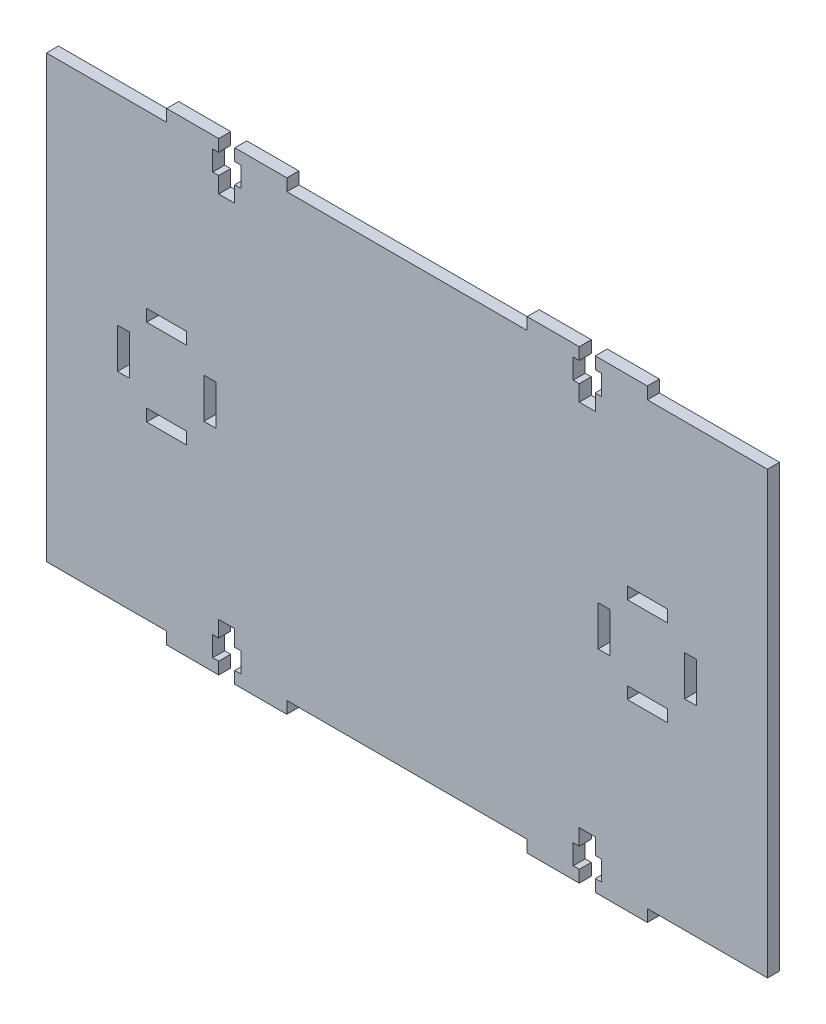
SolidWorks part; units mm, degrees
ref_plane "Front Plane" through (0, 0, 0) normal (0, 0, 1) x (1, 0, 0)
ref_plane "Top Plane" through (0, 0, 0) normal (0, 1, 0) x (1, 0, 0)
ref_plane "Right Plane" through (0, 0, 0) normal (1, 0, 0) x (0, 0, -1)
sketch "Sketch1" plane through (0, 0, 0) normal (0, 0, 1) x (1, 0, 0)
  line L0 (30, -55) -> (-30, -55)
  line L1 (-30, -55) -> (-30, -58)
  line L2 (30, -58) -> (30, -55)
  line L3 (-30, -58) -> (-43, -58)
  line L4 (43, -58) -> (30, -58)
  line L5 (-43, -58) -> (-43, -55)
  line L6 (43, -55) -> (43, -58)
  line L7 (-43, -55) -> (-41.5, -55)
  line L8 (41.5, -55) -> (43, -55)
  line L9 (-41.5, -55) -> (-41.5, -50)
  line L10 (41.5, -50) -> (41.5, -55)
  line L11 (-41.5, -50) -> (-43, -50)
  line L12 (43, -50) -> (41.5, -50)
  line L13 (-43, -50) -> (-43, -46)
  line L14 (43, -46) -> (43, -50)
  line L15 (-43, -46) -> (-47, -46)
  line L16 (47, -46) -> (43, -46)
  line L17 (-47, -46) -> (-47, -50)
  line L18 (47, -50) -> (47, -46)
  line L19 (-47, -50) -> (-48.5, -50)
  line L20 (48.5, -50) -> (47, -50)
  line L21 (-48.5, -50) -> (-48.5, -55)
  line L22 (48.5, -55) -> (48.5, -50)
  line L23 (-48.5, -55) -> (-47, -55)
  line L24 (47, -55) -> (48.5, -55)
  line L25 (-47, -55) -> (-47, -58)
  line L26 (47, -58) -> (47, -55)
  line L27 (-47, -58) -> (-60, -58)
  line L28 (60, -58) -> (47, -58)
  line L29 (-60, -58) -> (-60, -55)
  line L30 (60, -55) -> (60, -58)
  line L31 (-60, -55) -> (-90, -55)
  line L32 (90, -55) -> (60, -55)
  line L33 (-90, -55) -> (-90, 55)
  line L34 (90, 55) -> (90, -55)
  line L35 (-90, 55) -> (-60, 55)
  line L36 (60, 55) -> (90, 55)
  line L37 (-60, 55) -> (-60, 58)
  line L38 (60, 58) -> (60, 55)
  line L39 (-60, 58) -> (-47, 58)
  line L40 (47, 58) -> (60, 58)
  line L41 (-47, 58) -> (-47, 55)
  line L42 (47, 55) -> (47, 58)
  line L43 (-47, 55) -> (-48.5, 55)
  line L44 (48.5, 55) -> (47, 55)
  line L45 (-48.5, 55) -> (-48.5, 50)
  line L46 (48.5, 50) -> (48.5, 55)
  line L47 (-48.5, 50) -> (-47, 50)
  line L48 (47, 50) -> (48.5, 50)
  line L49 (-47, 50) -> (-47, 46)
  line L50 (47, 46) -> (47, 50)
  line L51 (-47, 46) -> (-43, 46)
  line L52 (43, 46) -> (47, 46)
  line L53 (-43, 46) -> (-43, 50)
  line L54 (43, 50) -> (43, 46)
  line L55 (-43, 50) -> (-41.5, 50)
  line L56 (41.5, 50) -> (43, 50)
  line L57 (-41.5, 50) -> (-41.5, 55)
  line L58 (41.5, 55) -> (41.5, 50)
  line L59 (-41.5, 55) -> (-43, 55)
  line L60 (43, 55) -> (41.5, 55)
  line L61 (-43, 55) -> (-43, 58)
  line L62 (43, 58) -> (43, 55)
  line L63 (-43, 58) -> (-30, 58)
  line L64 (30, 58) -> (43, 58)
  line L65 (-30, 58) -> (-30, 55)
  line L66 (30, 55) -> (30, 58)
  line L67 (-30, 55) -> (30, 55)
  line L68 (-61.5, -12.285) -> (-58.5, -12.285)
  line L69 (-58.5, -12.285) -> (-58.5, -9.285)
  line L70 (-61.5, -9.285) -> (-61.5, -12.285)
  line L71 (-58.5, -9.285) -> (-61.5, -9.285)
  line L72 (58.5, -12.285) -> (61.5, -12.285)
  line L73 (61.5, -12.285) -> (61.5, -9.285)
  line L74 (58.5, -9.285) -> (58.5, -12.285)
  line L75 (61.5, -9.285) -> (58.5, -9.285)
  line L76 (-72.285, -1.5) -> (-69.285, -1.5)
  line L77 (-69.285, -1.5) -> (-69.285, 1.5)
  line L78 (-72.285, 1.5) -> (-72.285, -1.5)
  line L79 (-69.285, 1.5) -> (-72.285, 1.5)
  line L80 (-50.715, -1.5) -> (-47.715, -1.5)
  line L81 (-47.715, -1.5) -> (-47.715, 1.5)
  line L82 (-50.715, 1.5) -> (-50.715, -1.5)
  line L83 (-47.715, 1.5) -> (-50.715, 1.5)
  line L84 (-61.5, 9.285) -> (-58.5, 9.285)
  line L85 (-58.5, 9.285) -> (-58.5, 12.285)
  line L86 (-61.5, 12.285) -> (-61.5, 9.285)
  line L87 (-58.5, 12.285) -> (-61.5, 12.285)
  line L88 (47.715, -1.5) -> (50.715, -1.5)
  line L89 (50.715, -1.5) -> (50.715, 1.5)
  line L90 (47.715, 1.5) -> (47.715, -1.5)
  line L91 (50.715, 1.5) -> (47.715, 1.5)
  line L92 (69.285, -1.5) -> (72.285, -1.5)
  line L93 (72.285, -1.5) -> (72.285, 1.5)
  line L94 (72.285, 1.5) -> (69.285, 1.5)
  line L95 (69.285, 1.5) -> (69.285, -1.5)
  line L96 (58.5, 9.285) -> (61.5, 9.285)
  line L97 (61.5, 9.285) -> (61.5, 12.285)
  line L98 (58.5, 12.285) -> (58.5, 9.285)
  line L99 (61.5, 12.285) -> (58.5, 12.285)
extrude "Plate_thickness_3mm" add sketch "Sketch1" along normal blind 3
sketch "草图1" plane through (0, 0, 3) normal (0, 0, 1) x (1, 0, 0)
  line L0 (-90, 0) -> (90, 0)
  line L1 (-90, 55) -> (-90, -55) construction
  line L2 (90, -55) -> (90, 55) construction
  line L3 (30, 55) -> (-30, 55) construction
  line L4 (0, 55) -> (0, -55)
  line L5 (-30, -55) -> (30, -55) construction
  line L6 (-65, -9.285) -> (-55, -9.285)
  line L7 (-72.285, 5) -> (-69.285, 5)
  line L8 (-72.285, 5) -> (-72.285, -5)
  line L9 (-72.285, -5) -> (-69.285, -5)
  line L10 (-69.285, 5) -> (-69.285, -5)
  line L11 (-72.285, 5) -> (-69.285, -5) construction
  line L12 (-72.285, -5) -> (-69.285, 5) construction
  line L13 (-50.715, 5) -> (-47.715, 5)
  line L14 (-50.715, 5) -> (-50.715, -5)
  line L15 (-50.715, -5) -> (-47.715, -5)
  line L16 (-47.715, 5) -> (-47.715, -5)
  line L17 (-50.715, 5) -> (-47.715, -5) construction
  line L18 (-50.715, -5) -> (-47.715, 5) construction
  line L19 (-65, 12.285) -> (-55, 12.285)
  line L20 (-65, 12.285) -> (-65, 9.285)
  line L21 (-65, 9.285) -> (-55, 9.285)
  line L22 (-55, 12.285) -> (-55, 9.285)
  line L23 (-65, 12.285) -> (-55, 9.285) construction
  line L24 (-65, 9.285) -> (-55, 12.285) construction
  line L29 (-55, -12.285) -> (-55, -9.285)
  line L30 (-65, -12.285) -> (-55, -12.285)
  line L31 (-65, -12.285) -> (-65, -9.285)
  line L32 (65, -12.285) -> (65, -9.285)
  line L33 (65, -12.285) -> (55, -12.285)
  line L34 (55, -12.285) -> (55, -9.285)
  line L35 (65, -9.285) -> (55, -9.285)
  line L36 (50.715, -5) -> (47.715, -5)
  line L37 (47.715, 5) -> (47.715, -5)
  line L38 (50.715, 5) -> (47.715, 5)
  line L39 (50.715, 5) -> (50.715, -5)
  line L40 (72.285, -5) -> (69.285, -5)
  line L41 (69.285, 5) -> (69.285, -5)
  line L42 (72.285, 5) -> (69.285, 5)
  line L43 (72.285, 5) -> (72.285, -5)
  line L44 (65, 9.285) -> (55, 9.285)
  line L45 (55, 12.285) -> (55, 9.285)
  line L46 (65, 12.285) -> (55, 12.285)
  line L47 (65, 12.285) -> (65, 9.285)
  point P12 (-70.785, 0)
  point P17 (-49.215, 0)
  point P22 (-60, 10.785)
  dimension "D1" = 10
  dimension "D2" = 10
  dimension "D3" = 10
  dimension "D5" = 18.57
  dimension "D6" = 4.285
extrude "切除-拉伸1" cut sketch "草图1" against normal up to surface (3 mm away) contours L31 L30 L29 L6 | L10 L0 L8 L9 | L10 L7 L8 L0 | L16 L13 L14 L0 | L16 L0 L14 L15 | L22 L19 L20 L21 | L47 L46 L45 L44 | L39 L38 L37 L0 | L39 L0 L37 L36 | L32 L35 L34 L33 | L43 L0 L41 L40 | L43 L42 L41 L0 up to face at (70.785, 0, 0)
